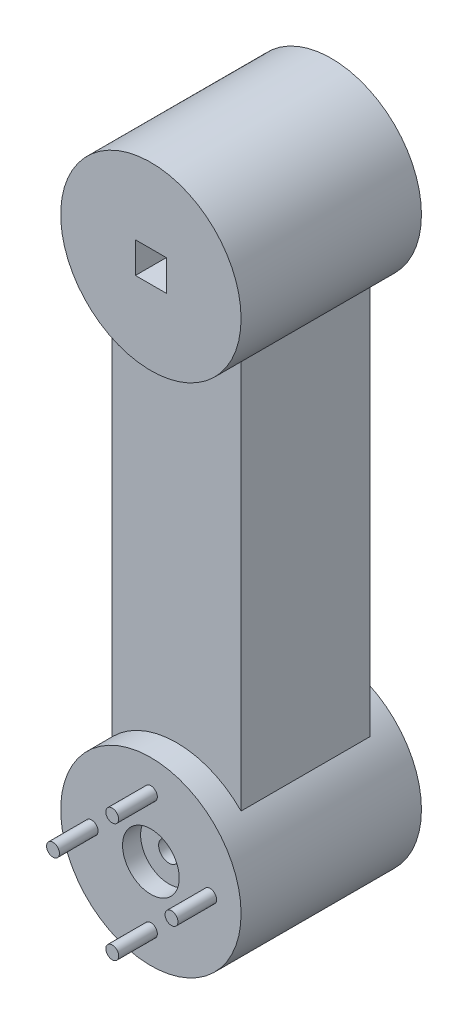
SolidWorks part; units mm, degrees
ref_plane "Alzado" through (0, 0, 0) normal (0, 0, 1) x (1, 0, 0)
ref_plane "Planta" through (0, 0, 0) normal (0, 1, 0) x (1, 0, 0)
ref_plane "Vista lateral" through (0, 0, 0) normal (1, 0, 0) x (0, 0, -1)
sketch "Croquis1" plane through (0, 0, 0) normal (0, 0, 1) x (1, 0, 0)
  circle A0 centre (0, 0) radius 35
  dimension "D1" = 70
extrude "Saliente-Extruir1" add sketch "Croquis1" along normal blind 70
sketch "Croquis2" plane through (0, 0, 0) normal (0, 1, 0) x (1, 0, 0)
  line L6 (-25, -60) -> (25, -60)
  line L7 (-25, -60) -> (-25, -10)
  line L8 (-25, -10) -> (25, -10)
  line L9 (25, -60) -> (25, -10)
  dimension "D2" = 50
  dimension "D3" = 50
extrude "Saliente-Extruir2" add sketch "Croquis2" along normal blind 200
sketch "Croquis4" plane through (0, 0, 0) normal (0, 0, 1) x (1, 0, 0)
  line L0 (-25, 200) -> (25, 200) construction
  circle A0 centre (0, 200) radius 35
  dimension "D1" = 70
extrude "Saliente-Extruir4" add sketch "Croquis4" along normal blind 70
sketch "Croquis5" plane through (0, 0, 0) normal (0, 0, 1) x (1, 0, 0)
  circle A0 centre (0, 0) radius 4
  dimension "D1" = 8
extrude "Cortar-Extruir1" cut sketch "Croquis5" along normal blind 150
sketch "Croquis6" plane through (0, 0, 0) normal (0, 0, 1) x (1, 0, 0)
  circle A0 centre (0, 0) radius 11
  dimension "D1" = 22
extrude "Cortar-Extruir3" cut sketch "Croquis6" along normal blind 7
ref_plane "Plano2" through (0, 0, 70) normal (0, 0, 1) x (1, 0, 0)
sketch "Croquis7" plane through (0, 0, 70) normal (0, 0, 1) x (1, 0, 0)
  circle A0 centre (0, 0) radius 11
  dimension "D1" = 22
extrude "Cortar-Extruir4" cut sketch "Croquis7" against normal blind 7
sketch "Croquis8" plane through (0, 0, 70) normal (0, 0, 1) x (1, 0, 0)
  circle A2 centre (-23, 0) radius 2.5
  circle A3 centre (0, -23) radius 2.5
  circle A4 centre (23, 0) radius 2.5
  circle A5 centre (0, 23) radius 2.5
  dimension "D5" = 5
  dimension "D6" = 5
  dimension "D7" = 5
  dimension "D8" = 5
extrude "Saliente-Extruir5" add sketch "Croquis8" along normal blind 15
sketch "Croquis9" plane through (0, 0, 70) normal (0, 0, 1) x (1, 0, 0)
  line L1 (-6, 206) -> (6, 206)
  line L2 (-6, 206) -> (-6, 194)
  line L3 (-6, 194) -> (6, 194)
  line L4 (6, 206) -> (6, 194)
  line L5 (-6, 206) -> (6, 194) construction
  line L6 (-6, 194) -> (6, 206) construction
  point P0 (0, 200)
  dimension "D1" = 12
  dimension "D2" = 12
extrude "Cortar-Extruir5" cut sketch "Croquis9" against normal blind 152
